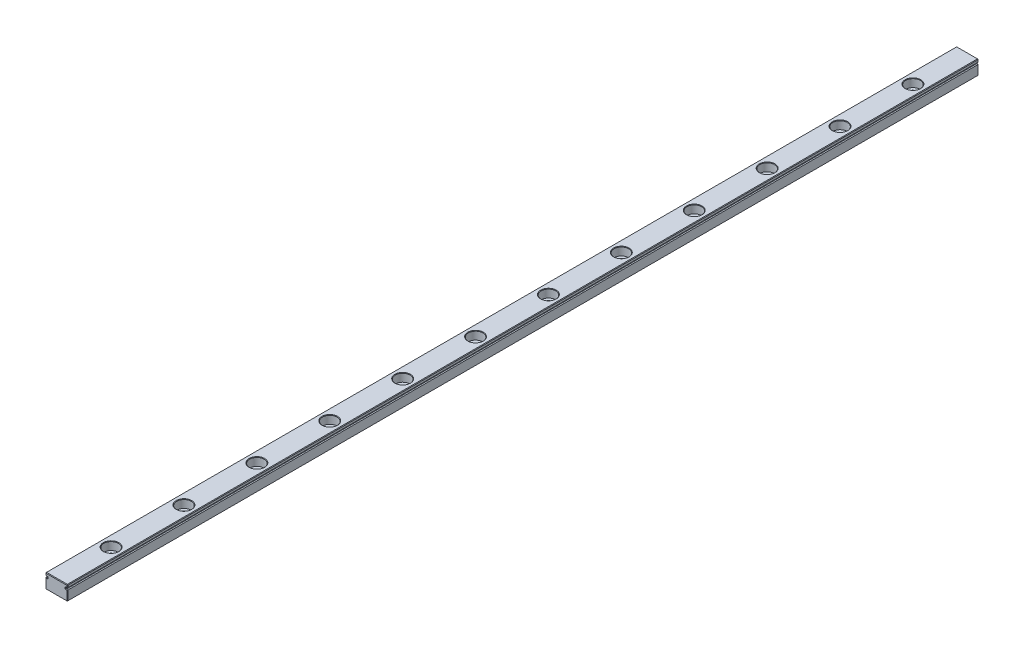
SolidWorks part; units mm, degrees
material "AISI 304"
ref_plane "Front Plane" through (0, 0, 0) normal (0, 0, 1) x (1, 0, 0)
ref_plane "Top Plane" through (0, 0, 0) normal (0, 1, 0) x (1, 0, 0)
ref_plane "Right Plane" through (0, 0, 0) normal (1, 0, 0) x (0, 0, -1)
sketch "Sketch1" plane through (0, 0, 0) normal (0, 0, 1) x (1, 0, 0)
  line L0 (0, 0) -> (0, 8) construction
  line L1 (0, 8) -> (12, 8)
  line L2 (0, 0) -> (12, 0)
  line L3 (0, 8) -> (0, 6.75)
  line L4 (0, 6.75) -> (0.5, 6.25) construction
  line L5 (0.5, 6.25) -> (1, 6.25)
  line L6 (0.5, 5.75) -> (0, 5.25) construction
  line L7 (0, 5.25) -> (0, 0)
  line L8 (1, 6.25) -> (1, 5.75)
  line L9 (1, 5.75) -> (0.5, 5.75)
  line L10 (0.5, 5.75) -> (0.75, 6) construction
  line L11 (0.75, 6) -> (0.5, 6.25) construction
  line L12 (0, 6.75) -> (0, 6.559)
  line L13 (0, 5.25) -> (0, 5.441)
  line L14 (6, 8) -> (6, 0) construction
  line L15 (11.25, 6) -> (11.5, 6.25) construction
  line L16 (11.5, 5.75) -> (11.25, 6) construction
  line L17 (11.5, 5.75) -> (12, 5.25) construction
  line L18 (12, 6.75) -> (11.5, 6.25) construction
  line L19 (12, 0) -> (12, 8) construction
  line L20 (12, 5.25) -> (12, 5.441)
  line L21 (12, 6.75) -> (12, 6.559)
  line L22 (11, 5.75) -> (11.5, 5.75)
  line L23 (11, 6.25) -> (11, 5.75)
  line L24 (12, 5.25) -> (12, 0)
  line L25 (11.5, 6.25) -> (11, 6.25)
  line L26 (12, 8) -> (12, 6.75)
  arc A0 (0, 5.441) -> (0.5, 5.75) centre (0, 6) ccw
  arc A1 (0.5, 6.25) -> (0, 6.559) centre (0, 6) ccw
  arc A2 (11.5, 6.25) -> (12, 6.559) centre (12, 6) cw
  arc A3 (12, 5.441) -> (11.5, 5.75) centre (12, 6) cw
  point P4 (1, 6)
  point P28 (11, 6)
  dimension "D1" = 8
  dimension "D2" = 6
  dimension "D3" = 0.5
  dimension "D4" = 45
  dimension "D5" = 2
  dimension "D6" = 1
extrude "Boss-Extrude1" add sketch "Sketch1" along normal blind 500
chamfer "Chamfer1" distance 0.3 angle 45 36 edges at (0, 0, 250) (12, 0, 250) (0, 8, 250) (12, 8, 250) (0.2939, 5.5245, 500) (0.75, 5.75, 500) (1, 6, 500) (0.75, 6.25, 500) (0.2939, 6.4755, 500) (0, 7.2795, 500) (6, 8, 500) (12, 7.2795, 500) (11.7061, 6.4755, 500) (11.25, 6.25, 500) (11, 6, 500) (11.25, 5.75, 500) (11.7061, 5.5245, 500) (12, 2.7205, 500) (6, 0, 500) (0, 2.7205, 500) (12, 2.7205, 0) (11.7061, 5.5245, 0) (11.25, 5.75, 0) (11, 6, 0) (11.25, 6.25, 0) (11.7061, 6.4755, 0) (12, 7.2795, 0) (6, 0, 0) (0, 2.7205, 0) (0.2939, 5.5245, 0) (0.75, 5.75, 0) (1, 6, 0) (0.75, 6.25, 0) (0.2939, 6.4755, 0) (0, 7.2795, 0) (6, 8, 0)
hole_wizard "CBORE for M5 Hex Head Bolt1" positions "3DSketch1" profile "Sketch3" counterbore size "M5" standard "ANSI Metric" end condition through all
sketch3d "3DSketch1"
  line L0 (6, 8, 0) -> (6, 8, 30) construction
  line L1 (11.7, 8, 0) -> (0.3, 8, 0) construction
  point P0 (6, 8, 30)
  dimension "D1" = 30
sketch "Sketch3" plane through (6, 8, 30) normal (1, 0, 0) x (0, 0, 1)
  line L0 (0, 0) -> (0, 8)
  line L1 (2.25, 7.75) -> (2.5, 8)
  line L2 (4, 4.5) -> (2.25, 4.5)
  line L3 (2.25, 4.5) -> (2.25, 7.75)
  line L5 (4, 4.5) -> (4, 0.25)
  line L6 (4, 0.25) -> (4.25, 0)
  line L7 (4.25, 0) -> (0, 0)
  line L8 (-4, 0.25) -> (-4.25, 0) construction
  line L11 (0, -6.35) -> (0, 107.95) construction
  line L12 (2.5, 8) -> (0, 8)
  line L13 (-2.25, 7.75) -> (-2.5, 8) construction
  dimension "Thru Hole Dia." = 4.5
  dimension "Thru Hole Depth" = 8
  dimension "C'Bore Dia." = 8
  dimension "C'Bore Depth" = 4.5
  dimension "Near C'Sink Dia." = 8.5
  dimension "Near C'Sink Angle" = 90
  dimension "Far C'Sink Dia." = 5
  dimension "Far C'Sink Angle" = 90
pattern_linear "LPattern1" count 12 spacing 40 along (0, 0, 1) of "CBORE for M5 Hex Head Bolt1"
ref_plane "Plan1" through (6, 0, 0) normal (1, 0, 0) x (0, 0, -1)
